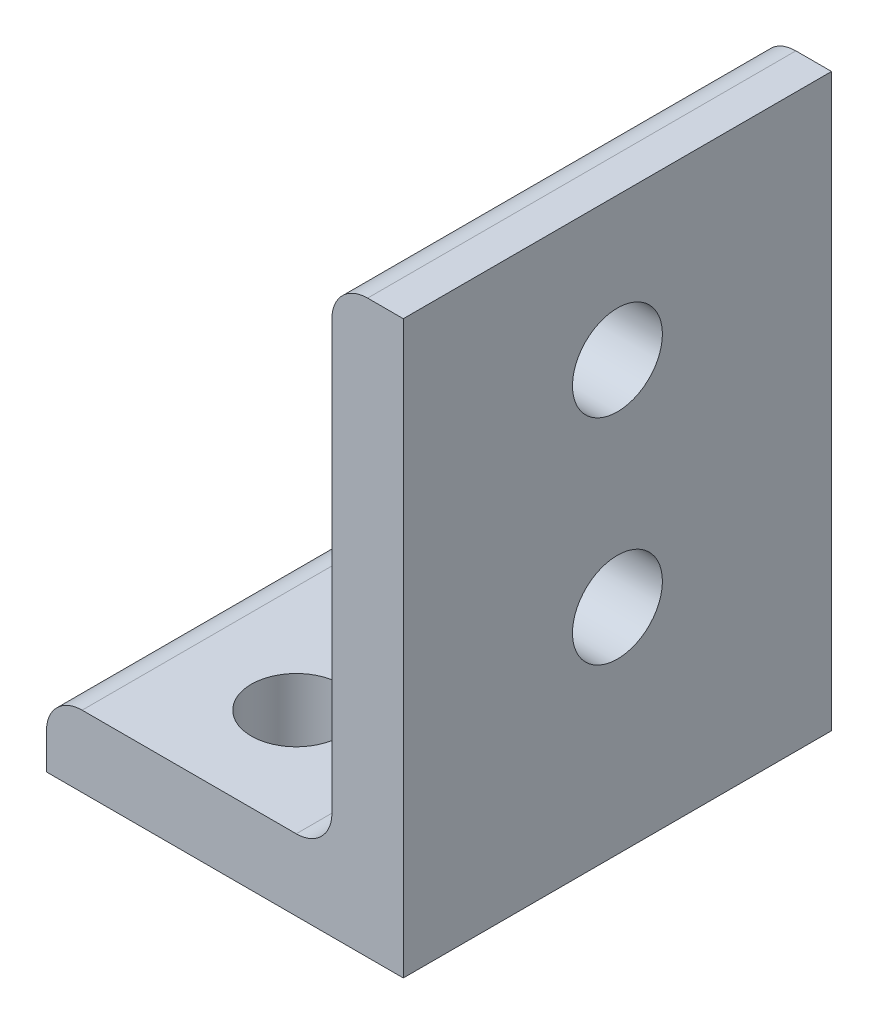
SolidWorks part; units mm, degrees
ref_plane "Front Plane" through (0, 0, 0) normal (0, 0, 1) x (1, 0, 0)
ref_plane "Top Plane" through (0, 0, 0) normal (0, 1, 0) x (1, 0, 0)
ref_plane "Right Plane" through (0, 0, 0) normal (1, 0, 0) x (0, 0, -1)
sketch "Sketch2" plane through (0, 0, 0) normal (0, 0, 1) x (1, 0, 0)
  line L0 (-15.875, 0) -> (15.875, 0)
  line L1 (15.875, 0) -> (15.875, 50.8)
  line L2 (15.875, 50.8) -> (9.525, 50.8) construction
  line L3 (9.525, 47.625) -> (9.525, 9.525)
  line L4 (6.35, 6.35) -> (-12.7, 6.35)
  line L5 (-15.875, 0) -> (-15.875, 6.35) construction
  line L6 (12.7, 50.8) -> (15.875, 50.8)
  line L7 (-15.875, 3.175) -> (-15.875, 0)
  arc A0 (9.525, 47.625) -> (12.7, 50.8) centre (12.7, 47.625) cw
  arc A1 (-15.875, 3.175) -> (-12.7, 6.35) centre (-12.7, 3.175) cw
  arc A2 (9.525, 9.525) -> (6.35, 6.35) centre (6.35, 9.525) cw
  dimension "Vert" = 50.8
  dimension "Horz" = 31.75
  dimension "Thickness" = 6.35
extrude "Boss-Extrude1" add sketch "Sketch2" along normal mid plane 38.1
ref_plane "Contact Plane 1" through (0, 6.35, 0) normal (0, 1, 0) x (1, 0, 0)
ref_plane "Contact Plane 2" through (9.525, 0, 0) normal (-1, 0, 0) x (0, 0, 1)
sketch "Sketch3" plane through (0, 6.35, 0) normal (0, 1, 0) x (1, 0, 0)
  line L0 (9.525, 0) -> (-15.875, 0) construction
  line L1 (-3.175, 0) -> (-3.175, 19.05) construction
  line L2 (-3.175, 19.05) -> (-3.175, 9.525) construction
  line L3 (9.525, -19.05) -> (9.525, 19.05) construction
  line L4 (-3.175, 9.525) -> (9.525, 9.525) construction
  line L7 (-15.875, -19.05) -> (-15.875, 19.05) construction
  line L8 (9.525, 9.525) -> (-3.175, 9.525) construction
  line L9 (6.35, 19.05) -> (-12.7, 19.05) construction
  line L10 (9.525, -9.525) -> (-3.175, -9.525) construction
  circle A2 centre (-3.175, 9.525) radius 4
  circle A4 centre (-3.175, -9.525) radius 4
  dimension "D1" = 8
  dimension "D3" = 9.525
extrude "Cut-Extrude1" cut sketch "Sketch3" against normal through all
sketch "Sketch4" plane through (9.525, 0, 0) normal (-1, 0, 0) x (0, 0, 1)
  line L0 (0, 47.625) -> (0, 9.525) construction
  line L1 (19.05, 47.625) -> (-19.05, 47.625) construction
  line L2 (19.05, 9.525) -> (-19.05, 9.525) construction
  line L3 (-19.05, 28.575) -> (19.05, 28.575) construction
  line L4 (-19.05, 47.625) -> (-19.05, 9.525) construction
  line L5 (19.05, 47.625) -> (19.05, 9.525) construction
  line L6 (19.05, 28.575) -> (19.05, 47.625) construction
  line L7 (19.05, 38.1) -> (-19.05, 38.1) construction
  circle A0 centre (0, 38.1) radius 4
  circle A1 centre (0, 19.05) radius 4
  circle A2 centre (0, 38.1) radius 7 construction
  dimension "D1" = 8
  dimension "D2" = 14
extrude "Cut-Extrude2" cut sketch "Sketch4" against normal through all
